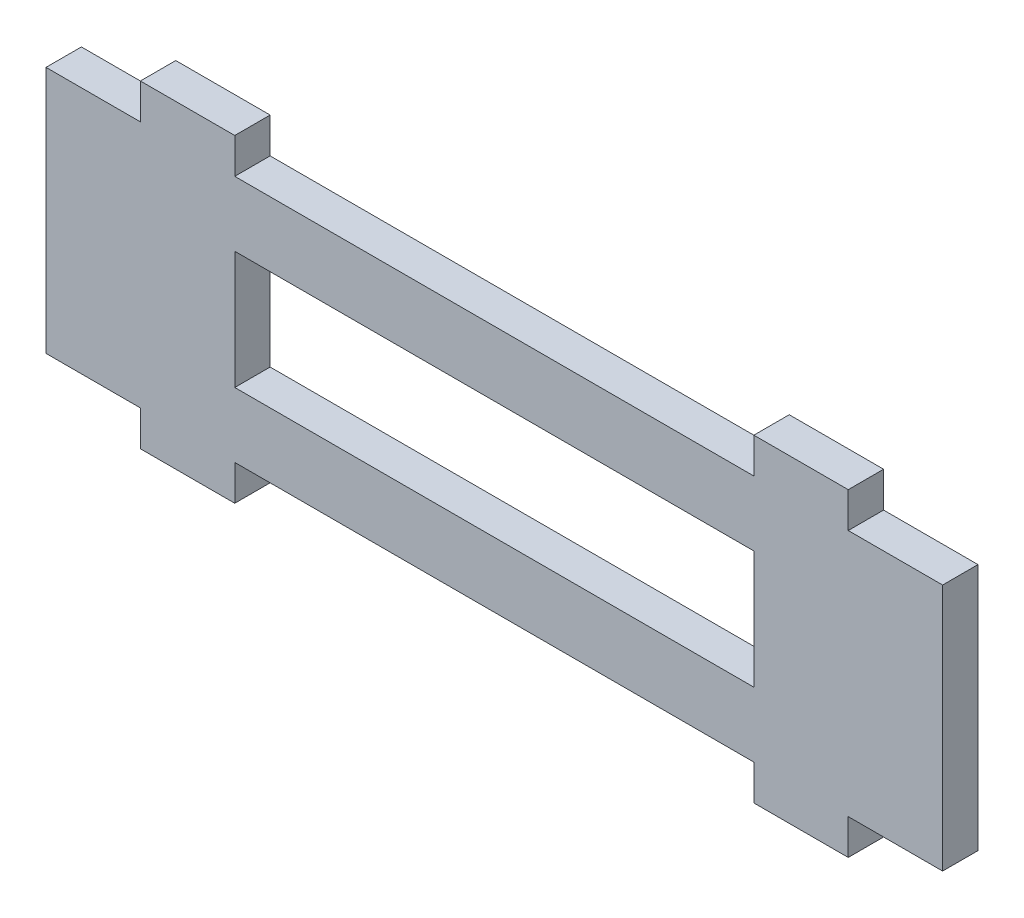
SolidWorks part; units mm, degrees
ref_plane "前视" through (0, 0, 0) normal (0, 0, 1) x (1, 0, 0)
ref_plane "上视" through (0, 0, 0) normal (0, 1, 0) x (1, 0, 0)
ref_plane "右视" through (0, 0, 0) normal (1, 0, 0) x (0, 0, -1)
sketch "草图1" plane through (0, 0, 0) normal (0, 0, 1) x (1, 0, 0)
  line L0 (-85.1376, 0) -> (95.3033, 0) construction
  line L1 (0, 78.9429) -> (0, -75.7661) construction
  line L2 (-38, -10.5) -> (-38, 10.5)
  line L3 (-38, 10.5) -> (-30, 10.5)
  line L4 (-30, 10.5) -> (-30, 13.5)
  line L5 (-30, 13.5) -> (-22, 13.5)
  line L6 (-22, 13.5) -> (-22, 10.5)
  line L7 (-22, 10.5) -> (22, 10.5)
  line L8 (-22, -10.5) -> (22, -10.5)
  line L9 (-22, -13.5) -> (-22, -10.5)
  line L10 (-30, -13.5) -> (-22, -13.5)
  line L11 (-30, -10.5) -> (-30, -13.5)
  line L12 (-38, -10.5) -> (-30, -10.5)
  line L14 (-22, -5) -> (22, -5)
  line L15 (-22, -5) -> (-22, 5)
  line L16 (-22, 5) -> (22, 5)
  line L17 (22, -5) -> (22, 5)
  line L18 (-22, -5) -> (22, 5) construction
  line L19 (-22, 5) -> (22, -5) construction
  line L23 (22, 13.5) -> (22, 10.5)
  line L24 (30, 13.5) -> (22, 13.5)
  line L25 (30, 10.5) -> (30, 13.5)
  line L26 (38, 10.5) -> (30, 10.5)
  line L31 (38, -10.5) -> (30, -10.5)
  line L32 (30, -10.5) -> (30, -13.5)
  line L33 (30, -13.5) -> (22, -13.5)
  line L34 (22, -13.5) -> (22, -10.5)
  line L39 (38, -10.5) -> (38, 10.5)
  point P13 (0, 0)
  point P18 (-38, 0)
  point P23 (0, 10.5)
  point P28 (0, -10.5)
  dimension "D1" = 10.5
  dimension "D2" = 22
  dimension "D3" = 8
  dimension "D4" = 38
  dimension "D5" = 3
  dimension "D6" = 3
  dimension "D7" = 10
  dimension "D8" = 44
extrude "凸台-拉伸1" add sketch "草图1" along normal blind 3
